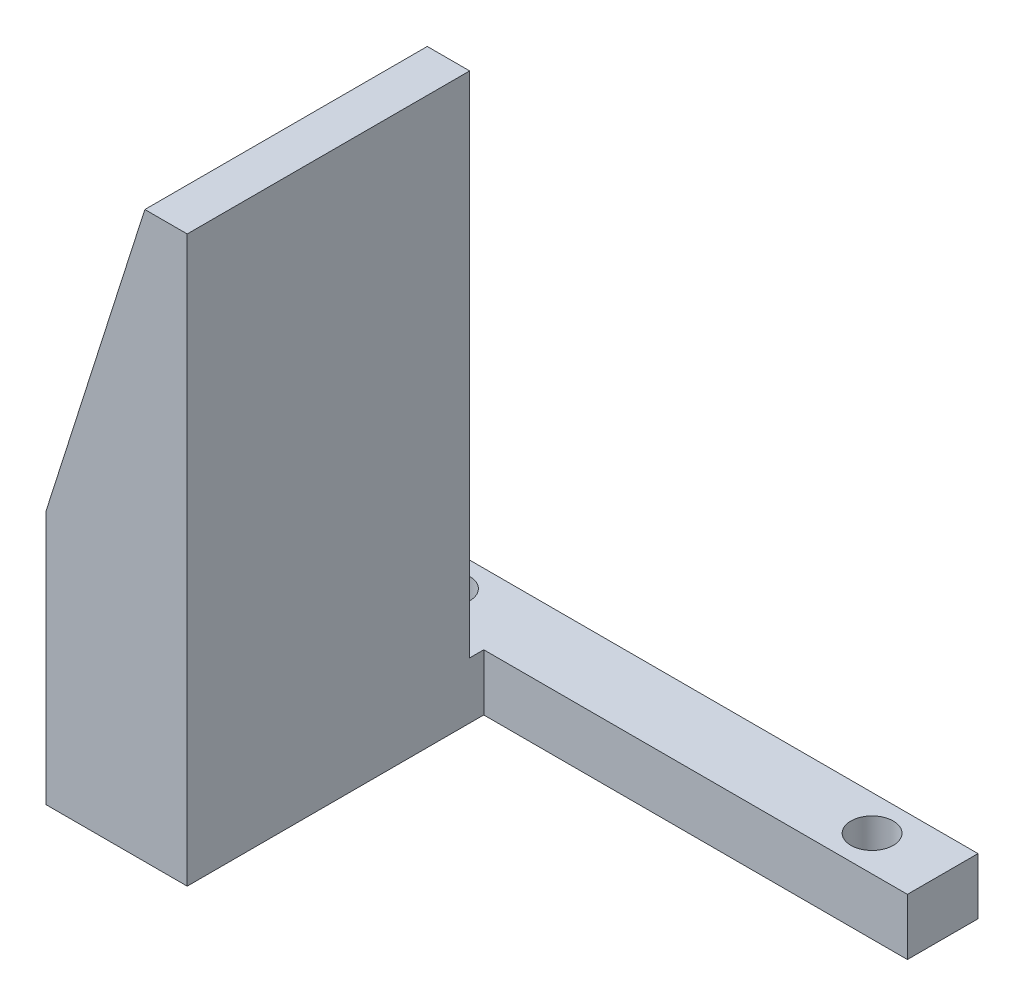
SolidWorks part; units mm, degrees
ref_plane "Front Plane" through (0, 0, 0) normal (0, 0, 1) x (1, 0, 0)
ref_plane "Top Plane" through (0, 0, 0) normal (0, 1, 0) x (1, 0, 0)
ref_plane "Right Plane" through (0, 0, 0) normal (1, 0, 0) x (0, 0, -1)
sketch "Sketch1" plane through (0, 0, 0) normal (0, 0, 1) x (1, 0, 0)
  line L0 (0, 0) -> (0, 40)
  line L1 (0, 40) -> (-3, 40)
  line L2 (-3, 40) -> (-10, 18)
  line L3 (-10, 18) -> (-10, 0)
  line L4 (-10, 0) -> (0, 0)
  dimension "D1" = 40
  dimension "D2" = 10
  dimension "D3" = 22
  dimension "D4" = 3
extrude "Boss-Extrude1" add sketch "Sketch1" along normal blind 20
sketch "Sketch2" plane through (0, 0, 0) normal (0, -1, 0) x (1, 0, 0)
  line L0 (-10, 0) -> (-10, -6)
  line L1 (-10, -6) -> (30, -6)
  line L2 (30, -6) -> (30, -1)
  line L3 (30, -1) -> (0, -1)
  line L4 (0, -1) -> (0, 0)
  line L5 (0, 0) -> (-10, 0)
  circle A0 centre (25, -3.5) radius 1.5
  circle A1 centre (-5, -3.5) radius 1.5
  point P12 (30, -3.5)
  point P13 (0, 0)
  dimension "D6" = 3
  dimension "D1" = 6
  dimension "D2" = 5
  dimension "D3" = 40
  dimension "D4" = 5
  dimension "D5" = 5
extrude "Boss-Extrude2" add sketch "Sketch2" against normal blind 4
